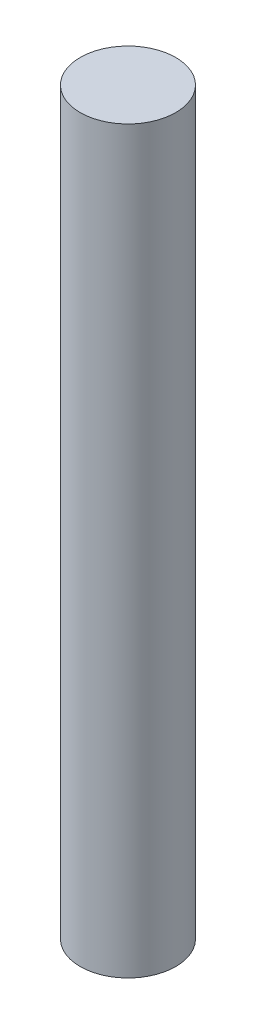
SolidWorks part; units mm, degrees
ref_plane "Plan de face" through (0, 0, 0) normal (0, 0, 1) x (1, 0, 0)
ref_plane "Plan de dessus" through (0, 0, 0) normal (0, 1, 0) x (1, 0, 0)
ref_plane "Plan de droite" through (0, 0, 0) normal (1, 0, 0) x (0, 0, -1)
sketch "Esquisse1" plane through (0, 0, 0) normal (0, 1, 0) x (1, 0, 0)
  circle A0 centre (0, 0) radius 1.55
  dimension "D1" = 3.1
extrude "Boss.-Extru.1" add sketch "Esquisse1" along normal blind 24
